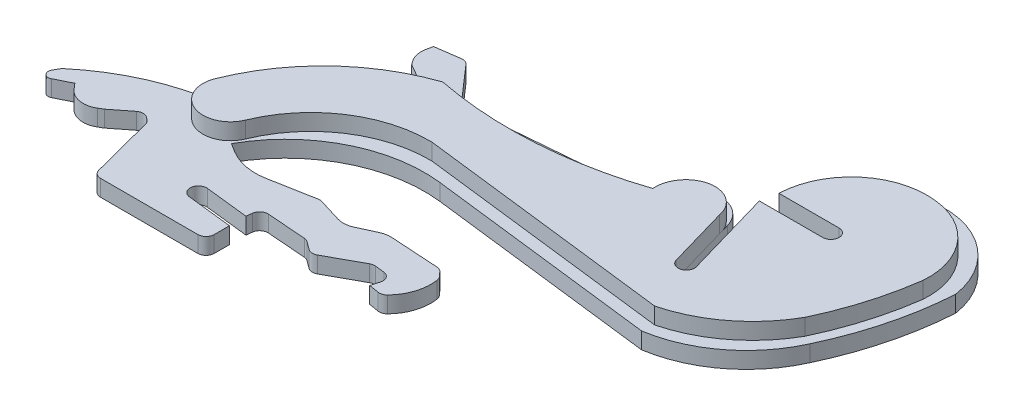
SolidWorks part; units mm, degrees
ref_plane "Front Plane" through (0, 0, 0) normal (0, 0, 1) x (1, 0, 0)
ref_plane "Top Plane" through (0, 0, 0) normal (0, 1, 0) x (1, 0, 0)
ref_plane "Right Plane" through (0, 0, 0) normal (1, 0, 0) x (0, 0, -1)
sketch "Sketch2" plane through (0, 0, 0) normal (0, 1, 0) x (1, 0, 0)
  line L28 (-42.5, 9.8153) -> (-40.2, 13.8486)
  line L29 (-36.6807, 12.7037) -> (-42.5, 9.8153)
  line L30 (-33.582, 9.1153) -> (-36.6807, 12.7037)
  line L31 (-29.8788, 11.3129) -> (-33.582, 9.1153)
  line L32 (4.26, 16.67) -> (10.265, 14.8219)
  line L33 (0, 0) -> (-20.44, 0)
  line L34 (22.2697, 7.6463) -> (24.8125, 7.2216)
  line L35 (23.2053, 10.8574) -> (22.2697, 7.6463)
  line L36 (19.2552, 11.2976) -> (23.2053, 10.8574)
  line L37 (11.8276, 7.2216) -> (19.2552, 11.2976)
  line L38 (9.25, 9.1) -> (11.8276, 7.2216)
  line L39 (0, 7.2986) -> (0.2788, 9.8)
  line L40 (-7.9231, 8.1815) -> (0, 7.2986)
  line L41 (0, 4.28) -> (-8.2554, 5.2)
  line L42 (0, 0) -> (0, 4.28)
  line L43 (-7.9231, 14.42) -> (4.26, 16.67)
  line L44 (-12.82, 17.46) -> (-7.9231, 14.42)
  line L45 (0.2788, 9.8) -> (9.25, 9.1)
  line L46 (10.265, 14.8219) -> (15.6812, 17.3217)
  line L47 (15.6812, 17.3217) -> (26.1051, 16.67)
  line L48 (26.1051, 16.67) -> (27.5, 15.12)
  line L49 (-20.44, 0) -> (-23.89, 13.229)
  line L50 (-23.89, 13.229) -> (-25.72, 14.58)
  line L51 (-25.72, 14.58) -> (-29.8788, 11.3129)
  line L52 (-4.89, 44.16) -> (-8.851, 46.4354)
  line L53 (-8.851, 46.4354) -> (-10.31, 48.4337)
  line L54 (-10.31, 48.4337) -> (-9.7196, 51.2866)
  line L55 (-9.7196, 51.2866) -> (-4.45, 52.03)
  line L56 (-4.45, 52.03) -> (2.1, 44.53)
  line L57 (2.1, 44.53) -> (35.22, 47.35)
  line L58 (12.44, 30.35) -> (54.32, 25.29)
  line L60 (48.0716, 56.63) -> (48.0108, 60.48)
  line L61 (52.1624, 37.4514) -> (49.2985, 47.38)
  line L62 (45.4508, 49.8957) -> (49.2717, 36.6497)
  line L63 (47.4956, 53.63) -> (49.2985, 47.38)
  line L64 (59.0716, 53.63) -> (47.4956, 53.63)
  line L65 (48.0716, 56.63) -> (59.0716, 56.63)
  arc A13 (-40.2, 13.8486) -> (-21.88, 22.46) centre (-15.2463, -15.4452) cw
  arc A14 (-21.88, 22.46) -> (-4.89, 44.16) centre (20.3443, 6.9017) cw
  arc A15 (24.8125, 7.2216) -> (27.5, 15.12) centre (19.6156, 13.3963) ccw
  arc A16 (-8.2554, 5.2) -> (-7.9231, 8.1815) centre (-8.0892, 6.6908) cw
  arc A17 (35.22, 47.35) -> (45.4508, 49.8957) centre (40.3825, 48.4337) cw
  arc A18 (49.2717, 36.6497) -> (52.1624, 37.4514) centre (50.7129, 37.0655) ccw
  arc A19 (59.0716, 56.63) -> (59.0716, 53.63) centre (59.0716, 55.13) cw
  arc A20 (48.0108, 60.48) -> (77.21, 59.8) centre (62.5507, 57.5772) cw
  arc A21 (77.21, 59.8) -> (71.72, 38.62) centre (18.8379, 63.6289) cw
  arc A22 (71.72, 38.62) -> (54.32, 25.29) centre (50.6354, 48.1209) cw
  arc A23 (12.44, 30.35) -> (-12.82, 17.46) centre (9.3925, 5.1266) ccw
  point P0 (77.21, 59.8)
  point P3 (51.1138, 35.62)
  point P4 (0, 0)
  point P5 (71.72, 38.62)
  point P6 (54.32, 25.29)
  point P8 (-4.89, 44.16)
  point P14 (12.44, 30.35)
  point P20 (35.22, 47.35)
  point P38 (57.5716, 55.13)
  point P53 (62.8959, 72.4)
  point P102 (27.5, 15.12)
  dimension "D6" = 53.63
  dimension "D11" = 9.8
  dimension "D32" = 17.46
  dimension "D33" = 12.82
  dimension "D34" = 4.26
  dimension "D35" = 21.88
  dimension "D36" = 22.46
  dimension "D37" = 25.72
  dimension "D38" = 67.7
  dimension "D39" = 4.89
  dimension "D40" = 44.16
  dimension "D75" = 14.8219
  dimension "D2" = 38.4812
  dimension "D4" = 20.44
  dimension "D5" = 8.0706
  dimension "D10" = 16.67
  dimension "D45" = 5.275
  dimension "D47" = 1.5
  dimension "D61" = 44.9994
  dimension "D62" = 14.8268
  dimension "D63" = 58.4976
  dimension "D64" = 23.1263
  dimension "D7" = 77.21
  dimension "D8" = 59.8
  dimension "D9" = 35.62
  dimension "D12" = 14.42
  dimension "D13" = 9.1
  dimension "D14" = 11.8276
  dimension "D15" = 14.58
  dimension "D16" = 19.2552
  dimension "D17" = 19.6156
  dimension "D18" = 73.91
  dimension "D19" = 22.2697
  dimension "D20" = 23.89
  dimension "D21" = 23.2053
  dimension "D22" = 24.8125
  dimension "D23" = 27.5
  dimension "D24" = 7.9231
  dimension "D25" = 8.0892
  dimension "D26" = 9.25
  dimension "D27" = 4.28
  dimension "D28" = 7.2216
  dimension "D29" = 7.6463
  dimension "D30" = 25.29
  dimension "D31" = 11.2976
  dimension "D41" = 44.53
  dimension "D42" = 47.35
  dimension "D43" = 52.03
  dimension "D44" = 35.22
  dimension "D46" = 6.25
  dimension "D48" = 10.076
  dimension "D49" = 54.32
  dimension "D50" = 38.62
  dimension "D51" = 3.85
  dimension "D52" = 71.72
  dimension "D53" = 30.35
  dimension "D54" = 12.44
  dimension "D55" = 72.4
  dimension "D56" = 11
  dimension "D57" = 10.31
  dimension "D58" = 2.1
  dimension "D59" = 4.45
  dimension "D60" = 70
  dimension "D65" = 10.265
  dimension "D66" = 15.6812
  dimension "D67" = 26.1051
  dimension "D68" = 40.3825
  dimension "D69" = 47.4956
  dimension "D70" = 9.1153
  dimension "D71" = 9.8153
  dimension "D72" = 11.3129
  dimension "D73" = 12.7037
  dimension "D74" = 13.229
  dimension "D76" = 17.3217
  dimension "D77" = 8.851
  dimension "D78" = 9.7196
  dimension "D79" = 15.2463
  dimension "D80" = 29.8788
  dimension "D81" = 33.582
  dimension "D82" = 36.6807
  dimension "D86" = 46.4354
  dimension "D87" = 51.2866
extrude "Boss-Extrude1" add sketch "Sketch2" along normal blind 3
fillet "Fillet1" radius 10 1 edges at (-7.9231, 1.5, -14.42)
fillet "Fillet2" radius 1 1 edges at (-42.5, 1.5, -9.8153)
fillet "Fillet3" radius 1.5 18 edges at (35.22, 1.5, -47.35) (-20.44, 1.5, 0) (0, 1.5, 0) (0.2788, 1.5, -9.8) (9.25, 1.5, -9.1) (19.2552, 1.5, -11.2976) (11.8276, 1.5, -7.2216) (26.1051, 1.5, -16.67) (27.5, 1.5, -15.12) (24.8125, 1.5, -7.2216) (23.2053, 1.5, -10.8574) (4.26, 1.5, -16.67) (-21.88, 1.5, -22.46) (-25.72, 1.5, -14.58) (-23.89, 1.5, -13.229) (-4.89, 1.5, -44.16) (-4.45, 1.5, -52.03) (2.1, 1.5, -44.53)
fillet "Fillet4" radius 4 2 edges at (-10.31, 1.5, -48.4337) (-33.582, 1.5, -9.1153)
fillet "Fillet5" radius 4 2 edges at (10.265, 1.5, -14.8219) (15.6812, 1.5, -17.3217)
sketch "Sketch3" plane through (0, 3, 0) normal (0, 1, 0) x (1, 0, 0)
  line L0 (47.4956, 53.63) -> (52.1624, 37.4514) construction
  line L1 (47.4956, 53.63) -> (52.1624, 37.4514)
  line L2 (49.2717, 36.6497) -> (45.4508, 49.8957) construction
  line L3 (48.0716, 56.63) -> (59.0716, 56.63) construction
  line L4 (59.0716, 53.63) -> (47.4956, 53.63) construction
  line L5 (49.2717, 36.6497) -> (46.0608, 47.7812)
  line L6 (48.0716, 56.63) -> (59.0716, 56.63)
  line L7 (59.0716, 53.63) -> (47.4956, 53.63)
  line L10 (12.6979, 32.4845) -> (54.5779, 27.4245)
  line L11 (8.2448, 33.0225) -> (54.5779, 27.4245)
  arc A0 (49.2717, 36.6497) -> (52.1624, 37.4514) centre (50.7129, 37.0655) ccw construction
  arc A1 (49.2717, 36.6497) -> (52.1624, 37.4514) centre (50.7129, 37.0655) ccw
  arc A2 (59.0716, 53.63) -> (59.0716, 56.63) centre (59.0716, 55.13) ccw construction
  arc A3 (59.0716, 53.63) -> (59.0716, 56.63) centre (59.0716, 55.13) ccw
  arc A4 (48.0716, 56.63) -> (63.6748, 69.7482) centre (61.8429, 56.0886) cw
  arc A5 (63.6748, 69.7482) -> (75.0218, 56.0147) centre (62.3118, 57.0677) cw
  arc A6 (35.7899, 45.8611) -> (39.5098, 51.5916) centre (41.356, 46.3206) cw
  arc A7 (39.5098, 51.5916) -> (46.0608, 47.7812) centre (41.1574, 46.8877) cw
  arc A8 (54.5779, 27.4245) -> (70.0928, 39.3895) centre (48.3114, 51.5916) ccw
  arc A9 (70.0928, 39.3895) -> (75.4139, 59.9178) centre (18.8379, 63.6289) ccw
  arc A10 (70.0928, 39.3895) -> (75.0218, 56.0147) centre (18.8379, 63.6289) ccw
  arc A11 (-0.2633, 43.5232) -> (-21.586, 23.2358) centre (11.0768, 10.2552) ccw
  arc A12 (-0.2633, 43.5232) -> (35.7899, 45.8611) centre (13.3304, 113.0509) ccw
  arc A13 (-21.586, 23.2358) -> (-12.2517, 19.4825) centre (-16.9113, 21.378) ccw
  arc A14 (-12.2517, 19.4825) -> (8.2448, 33.0225) centre (7.8785, 11.2935) cw
  dimension "D3" = 13.7819
  dimension "D4" = 12.7536
  dimension "D5" = 5.585
  dimension "D6" = 4.9841
  dimension "D7" = 24.9664
  dimension "D8" = 35.1476
  dimension "D9" = 70.8441
  dimension "D10" = 5.0304
  dimension "D11" = 21.7321
  dimension "D1" = 1.8
  dimension "D12" = 2.1882
  dimension "D13" = 13.5352
  dimension "D14" = 14.8982
  dimension "D15" = 31.1492
  dimension "D16" = 35.854
  dimension "D17" = 41.4201
  dimension "D18" = 63.8796
  dimension "D19" = 66.1332
  dimension "D20" = 68.9652
  dimension "D21" = 21.586
  dimension "D22" = 23.2358
  dimension "D2" = 2.15
extrude "Boss-Extrude2" add sketch "Sketch3" along normal blind 3 separate body
